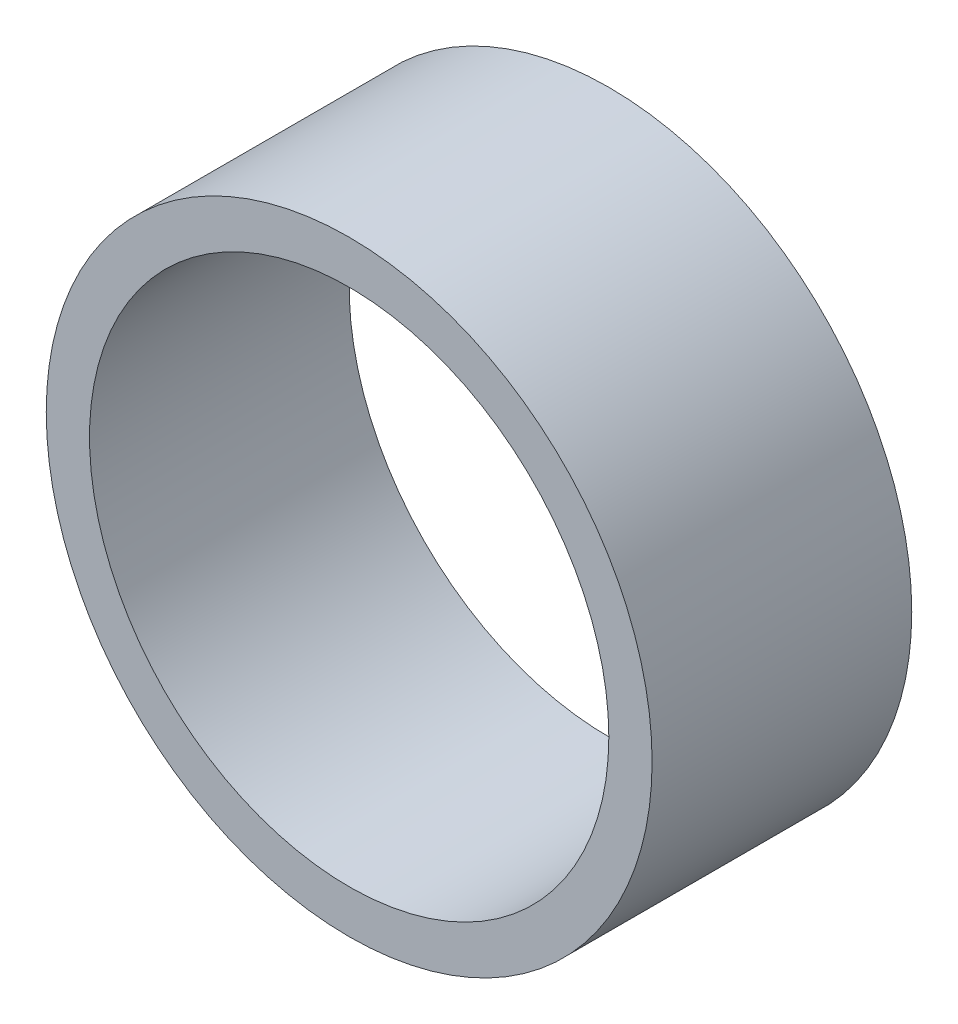
SolidWorks part; units mm, degrees
ref_plane "Front Plane" through (0, 0, 0) normal (0, 0, 1) x (1, 0, 0)
ref_plane "Top Plane" through (0, 0, 0) normal (0, 1, 0) x (1, 0, 0)
ref_plane "Right Plane" through (0, 0, 0) normal (1, 0, 0) x (0, 0, -1)
sketch "Sketch1" plane through (0, 0, 0) normal (0, 0, 1) x (1, 0, 0)
  circle A0 centre (0, 0) radius 15
  circle A1 centre (0, 0) radius 17.5
  dimension "D1" = 35
  dimension "D2" = 30
extrude "Boss-Extrude1" add sketch "Sketch1" along normal blind 15
